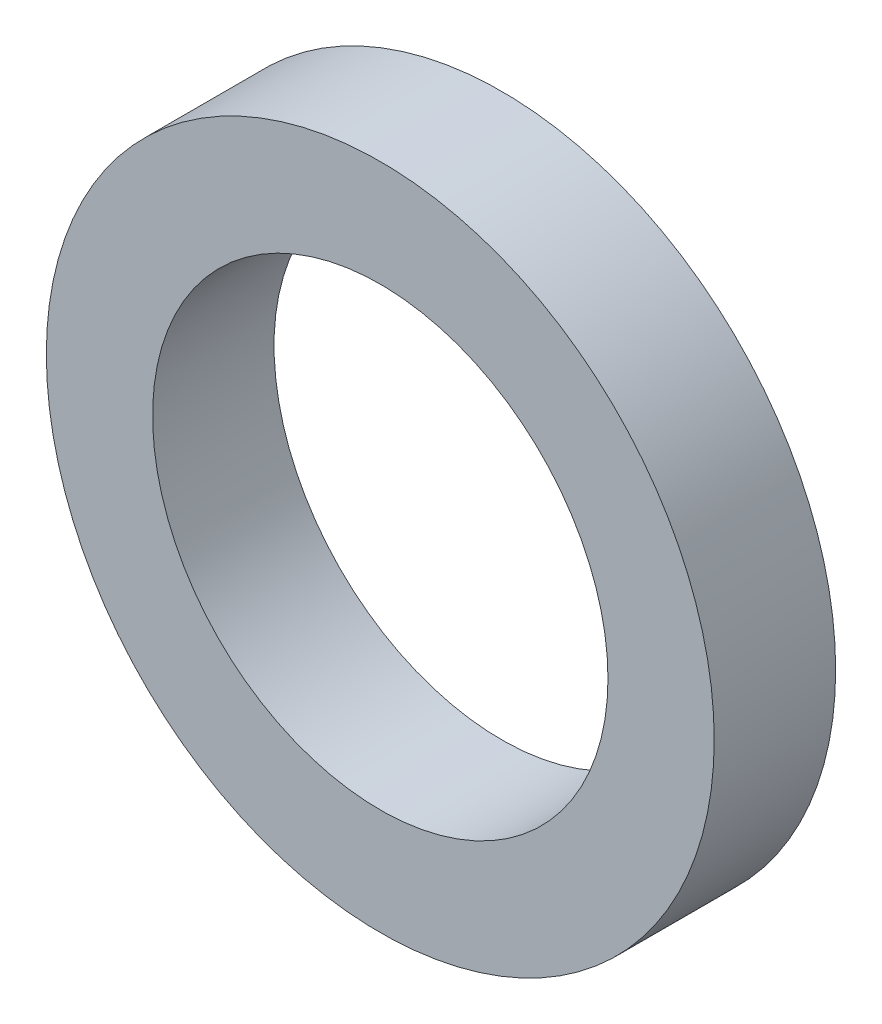
SolidWorks part; units mm, degrees
ref_plane "Alzado" through (0, 0, 0) normal (0, 0, 1) x (1, 0, 0)
ref_plane "Planta" through (0, 0, 0) normal (0, 1, 0) x (1, 0, 0)
ref_plane "Vista lateral" through (0, 0, 0) normal (1, 0, 0) x (0, 0, -1)
sketch "Croquis1" plane through (0, 0, 0) normal (0, 0, 1) x (1, 0, 0)
  circle A0 centre (0, 0) radius 3.75
  circle A1 centre (0, 0) radius 5.5
  dimension "D1" = 11
  dimension "D2" = 7.5
extrude "Saliente-Extruir1" add sketch "Croquis1" against normal blind 2
